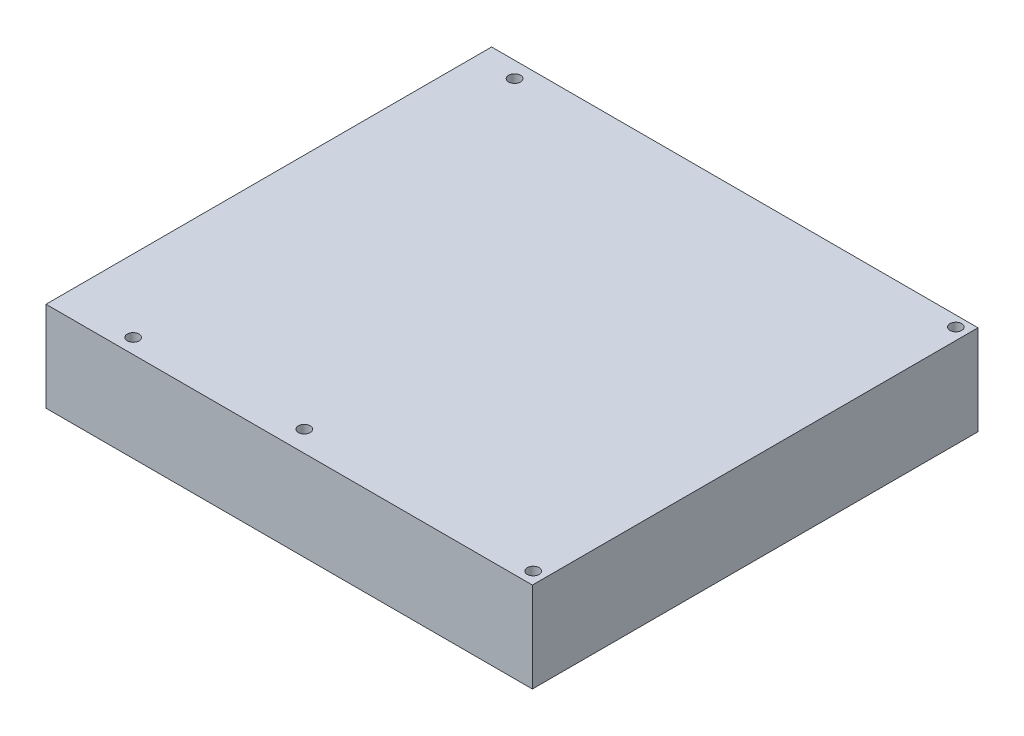
SolidWorks part; units mm, degrees
material "Epoxy, renforcé"
ref_plane "Plan de face" through (0, 0, 0) normal (0, 0, 1) x (1, 0, 0)
ref_plane "Plan de dessus" through (0, 0, 0) normal (0, 1, 0) x (1, 0, 0)
ref_plane "Plan de droite" through (0, 0, 0) normal (1, 0, 0) x (0, 0, -1)
sketch "Esquisse1" plane through (0, 0, 0) normal (0, 1, 0) x (1, 0, 0)
  line L1 (0, 0) -> (102.6, 0)
  line L2 (0, 0) -> (0, 94)
  line L3 (0, 94) -> (102.6, 94)
  line L4 (102.6, 0) -> (102.6, 94)
  dimension "D1" = 94
  dimension "D2" = 102.6
extrude "Boss.-Extru.1" add sketch "Esquisse1" along normal blind 19
sketch "Esquisse2" plane through (0, 19, 0) normal (0, 1, 0) x (1, 0, 0)
  circle A0 centre (8.1988, 90.6381) radius 1.25
  circle A1 centre (100.1261, 91.7999) radius 1.25
  circle A2 centre (100.1261, 2.6404) radius 1.25
  circle A3 centre (50.0635, 4.4221) radius 1.25
  circle A4 centre (15.259, 3.1221) radius 1.25
  dimension "D1" = 2.5
extrude "Enlèv. mat.-Extru.1" cut sketch "Esquisse2" against normal through all
